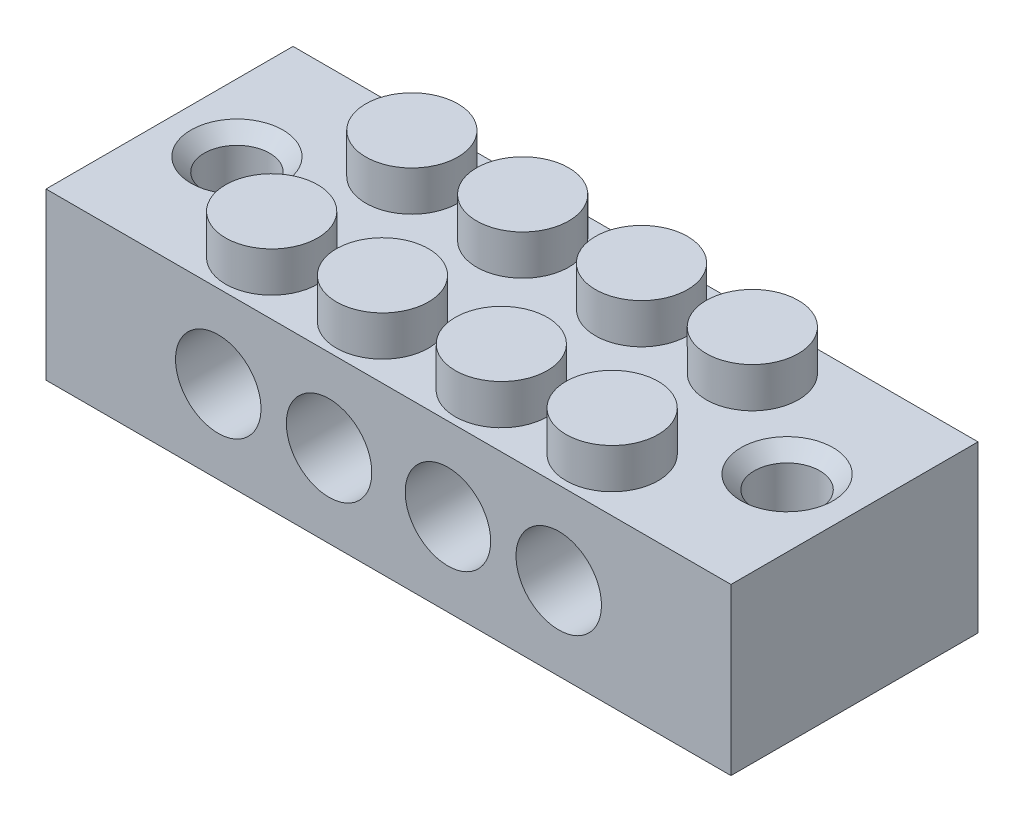
SolidWorks part; units mm, degrees
ref_plane "Front Plane" through (0, 0, 0) normal (0, 0, 1) x (1, 0, 0)
ref_plane "Top Plane" through (0, 0, 0) normal (0, 1, 0) x (1, 0, 0)
ref_plane "Right Plane" through (0, 0, 0) normal (1, 0, 0) x (0, 0, -1)
sketch "Sketch1" plane through (0, 0, 0) normal (0, 1, 0) x (1, 0, 0)
  line L1 (25.65, -9.25) -> (-25.65, -9.25)
  line L2 (25.65, -9.25) -> (25.65, 9.25)
  line L3 (25.65, 9.25) -> (-25.65, 9.25)
  line L4 (-25.65, -9.25) -> (-25.65, 9.25)
  line L5 (25.65, -9.25) -> (-25.65, 9.25) construction
  line L6 (25.65, 9.25) -> (-25.65, -9.25) construction
  point P0 (0, 0)
  dimension "D1" = 51.3
  dimension "D2" = 18.5
extrude "Boss-Extrude1" add sketch "Sketch1" along normal blind 12.4
sketch "Sketch2" plane through (0, 0, 9.25) normal (0, 0, 1) x (1, 0, 0)
  line L0 (-25.65, 6.2) -> (25.65, 6.2) construction
  line L1 (-25.65, 12.4) -> (-25.65, 0) construction
  line L2 (25.65, 12.4) -> (25.65, 0) construction
  circle A0 centre (4.45, 6.2) radius 3.2
  circle A1 centre (12.75, 6.2) radius 3.2
  point P11 (0, 6.2)
  dimension "D1" = 6.4
  dimension "D3" = 9.55
  dimension "D2" = 1.25
extrude "Cut-Extrude1" cut sketch "Sketch2" against normal through all
sketch "Sketch3" plane through (0, 12.4, 0) normal (0, 1, 0) x (1, 0, 0)
  line L0 (0, 0) -> (18.15, 0) construction
  circle A0 centre (20.6, 0) radius 2.45
  point P4 (18.15, 0)
  point P6 (0, 0)
  dimension "D2" = 4.9
  dimension "D1" = 18.15
extrude "Cut-Extrude2" cut sketch "Sketch3" against normal through all
mirror "Mirror1" about plane through (0, 0, 0) normal (1, 0, 0) of "Cut-Extrude2", "Cut-Extrude1"
chamfer "Chamfer1" distance 1 angle 45 2 edges at (20.6, 12.4, 2.45) (-20.6, 12.4, 2.45)
sketch "Sketch4" plane through (0, 12.4, 0) normal (0, 1, 0) x (1, 0, 0)
  line L0 (4.45, -9.25) -> (4.45, 9.25) construction
  line L1 (25.65, 9.25) -> (-25.65, 9.25) construction
  line L2 (12.75, -9.25) -> (12.75, 9.25) construction
  line L3 (4.45, 0) -> (12.75, 0) construction
  circle A0 centre (4.45, -5.25) radius 3.45
  circle A1 centre (12.75, -5.25) radius 3.45
  point P0 (12.75, -9.25)
  point P2 (4.45, -9.25)
  point P16 (0, 0)
  dimension "D1" = 6.9
  dimension "D2" = 1.8
extrude "Boss-Extrude2" add sketch "Sketch4" along normal blind 3
mirror "Mirror2" about plane through (0, 0, 0) normal (0, 0, 1) of "Boss-Extrude2"
mirror "Mirror3" about plane through (0, 0, 0) normal (1, 0, 0) of "Mirror2", "Boss-Extrude2"
